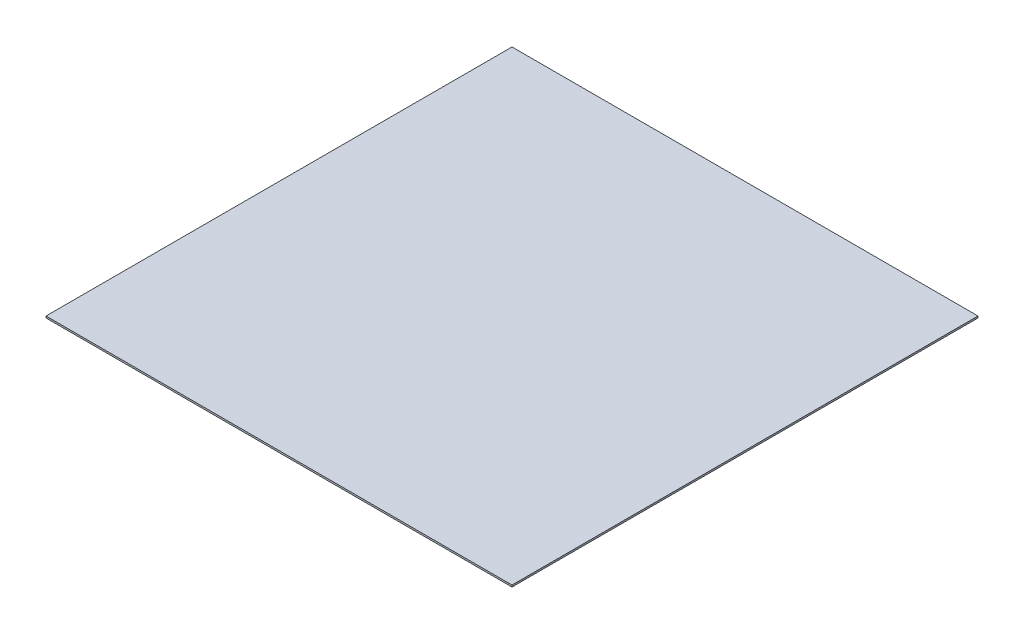
SolidWorks part; units mm, degrees
ref_plane "Front Plane" through (0, 0, 0) normal (0, 0, 1) x (1, 0, 0)
ref_plane "Top Plane" through (0, 0, 0) normal (0, 1, 0) x (1, 0, 0)
ref_plane "Right Plane" through (0, 0, 0) normal (1, 0, 0) x (0, 0, -1)
sketch "Sketch2" plane through (0, 0, 0) normal (0, 1, 0) x (1, 0, 0)
  line L1 (-400, 400) -> (400, 400)
  line L2 (-400, 400) -> (-400, -400)
  line L3 (-400, -400) -> (400, -400)
  line L4 (400, 400) -> (400, -400)
  line L5 (-400, 400) -> (400, -400) construction
  line L6 (-400, -400) -> (400, 400) construction
  point P0 (0, 0)
  dimension "D1" = 800
  dimension "D2" = 800
extrude "Boss-Extrude1" add sketch "Sketch2" along normal blind 3 contours L1 L4 L3 L2
sketch "Sketch3" plane through (0, 3, 0) normal (0, 1, 0) x (1, 0, 0)
  line L0 (-348, -172.5) -> (348, -172.5) construction
  line L1 (-360, 360) -> (360, 360)
  line L2 (-360, 360) -> (-360, -360)
  line L3 (-360, -360) -> (360, -360)
  line L4 (360, 360) -> (360, -360)
  line L5 (-360, 360) -> (360, -360) construction
  line L6 (-360, -360) -> (360, 360) construction
  line L7 (348, -187.5) -> (-348, -187.5) construction
  line L8 (-187.5, 348) -> (-187.5, -348) construction
  line L9 (-360, 180) -> (360, 180)
  line L10 (-348, 348) -> (348, 348) construction
  line L11 (-348, 348) -> (-348, -348) construction
  line L12 (-348, -348) -> (348, -348) construction
  line L13 (348, 348) -> (348, -348) construction
  line L14 (-348, 348) -> (348, -348) construction
  line L15 (-348, -348) -> (348, 348) construction
  line L16 (-363, 363) -> (363, 363) construction
  line L17 (-363, 363) -> (-363, -363) construction
  line L18 (-363, -363) -> (363, -363) construction
  line L19 (363, 363) -> (363, -363) construction
  line L20 (-363, 363) -> (363, -363) construction
  line L21 (-363, -363) -> (363, 363) construction
  line L22 (-360, 0) -> (360, 0)
  line L23 (-360, -180) -> (360, -180)
  line L24 (-180, 360) -> (-180, -360)
  line L25 (0, 360) -> (0, -360)
  line L26 (180, 360) -> (180, -360)
  line L27 (-348, 187.5) -> (348, 187.5) construction
  line L28 (-348, 172.5) -> (348, 172.5) construction
  line L29 (-348, 7.5) -> (348, 7.5) construction
  line L30 (348, -7.5) -> (-348, -7.5) construction
  line L31 (-172.5, -348) -> (-172.5, 348) construction
  line L32 (-7.5, 348) -> (-7.5, -348) construction
  line L33 (7.5, -348) -> (7.5, 348) construction
  line L34 (172.5, -348) -> (172.5, 348) construction
  line L35 (187.5, 348) -> (187.5, -348) construction
  point P0 (0, 0)
  point P6 (0, 0)
  point P10 (0, 0)
  dimension "D1" = 720
  dimension "D2" = 720
  dimension "D3" = 696
  dimension "D4" = 726
  dimension "D5" = 726
  dimension "D6" = 180
  dimension "D7" = 180
  dimension "D8" = 180
  dimension "D9" = 180
  dimension "D10" = 180
  dimension "D11" = 180
  dimension "D12" = 15
  dimension "D13" = 15
  dimension "D14" = 7.5
  dimension "D15" = 7.5
  dimension "D16" = 15
  dimension "D17" = 15
  dimension "D18" = 7.5
  dimension "D19" = 15
  dimension "D20" = 15
  dimension "D21" = 15
  dimension "D22" = 15
  dimension "D23" = 15
